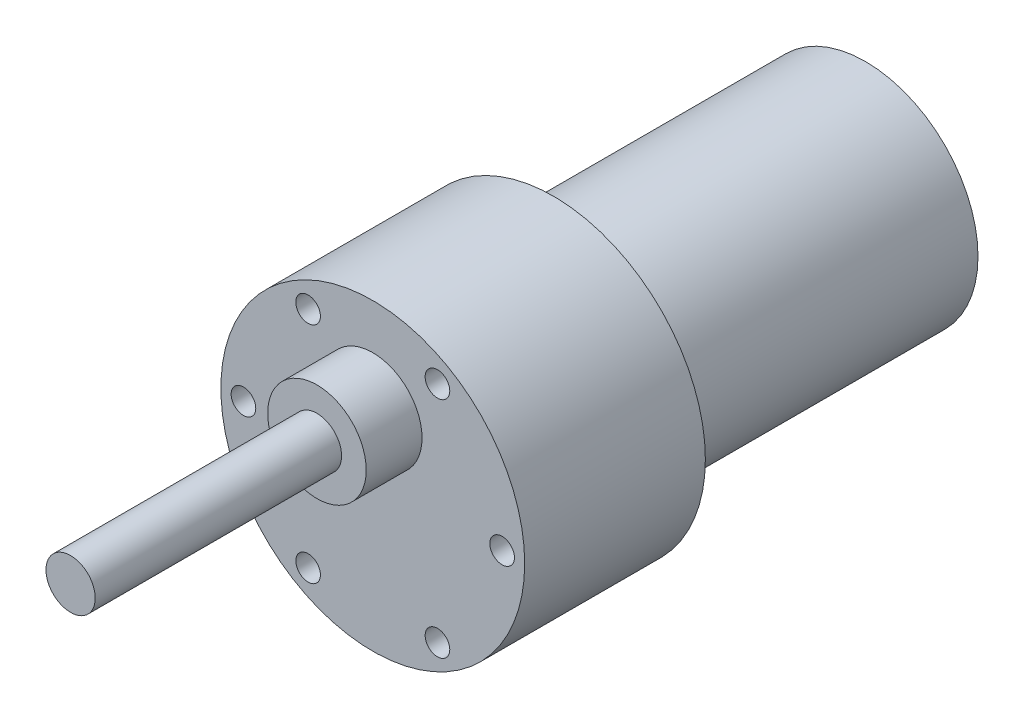
SolidWorks part; units mm, degrees
ref_plane "Front Plane" through (0, 0, 0) normal (0, 0, 1) x (1, 0, 0)
ref_plane "Top Plane" through (0, 0, 0) normal (0, 1, 0) x (1, 0, 0)
ref_plane "Right Plane" through (0, 0, 0) normal (1, 0, 0) x (0, 0, -1)
sketch "Sketch1" plane through (0, 0, 0) normal (0, 0, 1) x (1, 0, 0)
  circle A0 centre (0, 0) radius 13.7
extrude "Boss-Extrude1" add sketch "Sketch1" along normal blind 38
sketch "Sketch2" plane through (0, 0, 38) normal (0, 0, 1) x (1, 0, 0)
  circle A0 centre (0, 0) radius 18.5
extrude "Boss-Extrude2" add sketch "Sketch2" along normal blind 22
sketch "Sketch3" plane through (0, 0, 60) normal (0, 0, 1) x (1, 0, 0)
  line L0 (-24.9022, 0) -> (23.7037, 0) construction
  circle A0 centre (0, 7) radius 6
  dimension "D1" = 7
extrude "Boss-Extrude3" add sketch "Sketch3" along normal blind 6.8
sketch "Sketch4" plane through (0, 0, 66.8) normal (0, 0, 1) x (1, 0, 0)
  circle A0 centre (0, 7) radius 3
extrude "Boss-Extrude4" add sketch "Sketch4" along normal blind 30
sketch "Sketch5" plane through (0, 0, 60) normal (0, 0, 1) x (1, 0, 0)
  circle A0 centre (-15.75, 0) radius 1.5
  circle A1 centre (-7.875, 13.6399) radius 1.5
  circle A2 centre (7.875, 13.6399) radius 1.5
  circle A3 centre (15.75, 0) radius 1.5
  circle A4 centre (7.875, -13.6399) radius 1.5
  circle A5 centre (-7.875, -13.6399) radius 1.5
  point P2 (0, 0)
  point P17 (0, 0)
  dimension "D1" = 15.75
  dimension "D2" = 6
extrude "Cut-Extrude1" cut sketch "Sketch5" against normal blind 5
